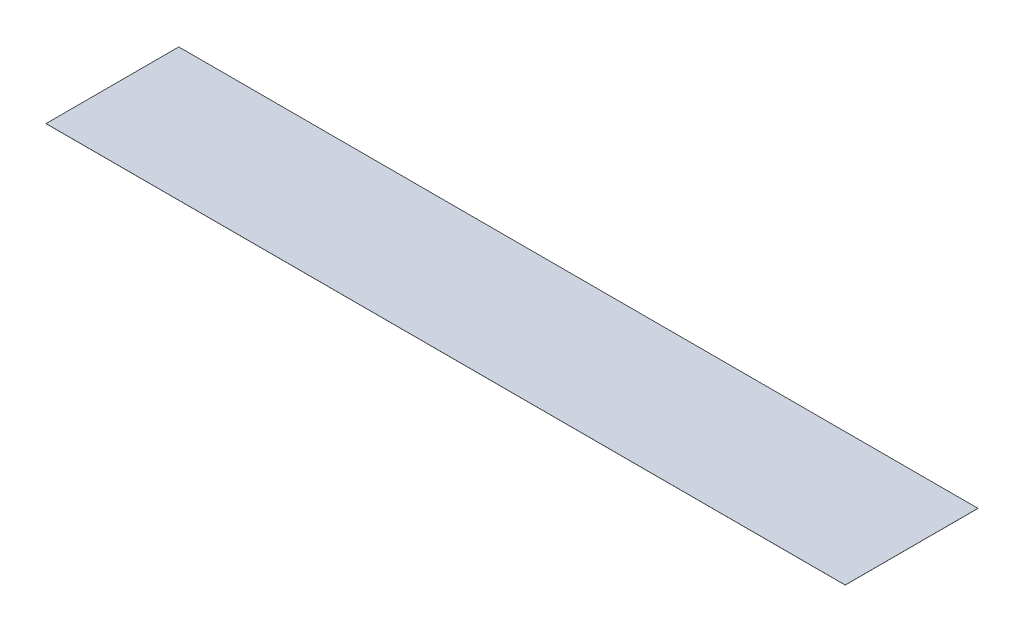
SolidWorks part; units mm, degrees
ref_plane "Plano frontal" through (0, 0, 0) normal (0, 0, 1) x (1, 0, 0)
ref_plane "Plano superior" through (0, 0, 0) normal (0, 1, 0) x (1, 0, 0)
ref_plane "Plano direito" through (0, 0, 0) normal (1, 0, 0) x (0, 0, -1)
sketch "Esboço1" plane through (0, 0, 0) normal (0, 1, 0) x (1, 0, 0)
  line L0 (-1093, 595.536) -> (-1073, 595.536)
  line L1 (0, 0) -> (18.9344, 0)
  line L2 (0, 0) -> (0, 766.8662)
  line L3 (0, 766.8662) -> (18.9344, 766.8662)
  line L4 (18.9344, 0) -> (18.9344, 766.8662)
  line L5 (-381.6968, 766.8662) -> (-362.7624, 766.8662)
  line L6 (-381.6968, 766.8662) -> (-381.6968, 345.536)
  line L7 (-381.6968, 345.536) -> (-362.7624, 345.536)
  line L8 (-362.7624, 766.8662) -> (-362.7624, 345.536)
  line L9 (-858.9344, 645.536) -> (-840, 645.536)
  line L10 (-858.9344, 645.536) -> (-858.9344, 345.536)
  line L11 (-858.9344, 345.536) -> (-840, 345.536)
  line L12 (-840, 645.536) -> (-840, 345.536)
  line L13 (-853.5858, 925.2213) -> (-1253.5858, 925.2213)
  line L14 (-853.5858, 925.2213) -> (-853.5858, 945.2213)
  line L15 (-853.5858, 945.2213) -> (-1253.5858, 945.2213)
  line L16 (-1253.5858, 925.2213) -> (-1253.5858, 945.2213)
  line L17 (-1093, 595.536) -> (-1093, 195.536)
  line L18 (-1093, 195.536) -> (-1073, 195.536)
  line L19 (-1073, 595.536) -> (-1073, 195.536)
  line L21 (-858.9344, 427.7897) -> (-1250.0103, 427.7897)
  line L23 (-858.9344, 407.7897) -> (-1250.0103, 407.7897)
  line L24 (-1250.0103, 427.7897) -> (-1250.0103, 407.7897)
  line L33 (-1439.6613, 239.7512) -> (-1560.0448, 239.7512)
  line L34 (-1439.6613, 239.7512) -> (-1439.6613, 219.7512)
  line L35 (-1439.6613, 219.7512) -> (-1560.0448, 219.7512)
  line L36 (-1560.0448, 239.7512) -> (-1560.0448, 219.7512)
  line L37 (-1627.2015, 576.144) -> (-1607.2015, 576.144)
  line L38 (-1627.2015, 576.144) -> (-1627.2015, 317.0654)
  line L39 (-1627.2015, 317.0654) -> (-1607.2015, 317.0654)
  line L40 (-1607.2015, 576.144) -> (-1607.2015, 317.0654)
  line L41 (-1627.2015, 769.6927) -> (-1607.2015, 769.6927)
  line L42 (-1627.2015, 769.6927) -> (-1627.2015, 1019.6927)
  line L43 (-1627.2015, 1019.6927) -> (-1607.2015, 1019.6927)
  line L44 (-1607.2015, 769.6927) -> (-1607.2015, 1019.6927)
  line L45 (-1714.3168, 276.905) -> (-1834.7003, 276.905)
  line L46 (-1714.3168, 276.905) -> (-1714.3168, 256.905)
  line L47 (-1714.3168, 256.905) -> (-1834.7003, 256.905)
  line L48 (-1834.7003, 276.905) -> (-1834.7003, 256.905)
  arc A6 (-381.6968, 766.8662) -> (18.9344, 766.8662) centre (-181.3812, 766.8662) cw
  arc A7 (-362.7624, 766.8662) -> (0, 766.8662) centre (-181.3812, 766.8662) cw
  arc A8 (-362.7624, 345.536) -> (-858.9344, 345.536) centre (-610.8484, 345.536) cw
  arc A9 (-381.6968, 345.536) -> (-840, 345.536) centre (-610.8484, 345.536) cw
  arc A10 (-840, 645.536) -> (-803.6955, 702.0415) centre (-777.8744, 645.536) cw
  arc A11 (-803.6955, 702.0415) -> (-853.5858, 945.2213) centre (-856.6336, 817.8884) ccw
  arc A12 (-858.9344, 645.536) -> (-814.4955, 717.9247) centre (-777.7563, 645.536) cw
  arc A13 (-814.4955, 717.9247) -> (-853.5858, 925.2213) centre (-864.2122, 815.8835) ccw
  arc A14 (-1093, 595.536) -> (-1188.5366, 677.9223) centre (-1176.2913, 595.536) ccw
  arc A15 (-1188.5366, 677.9223) -> (-1354.3411, 742.8189) centre (-1214.8489, 854.9525) cw
  arc A16 (-1354.3411, 742.8189) -> (-1253.5858, 945.2213) centre (-1257.3278, 820.805) cw
  arc A17 (-1073, 595.536) -> (-1188.5366, 698.0004) centre (-1176.2038, 595.536) ccw
  arc A18 (-1188.5366, 698.0004) -> (-1341.8208, 766.8662) centre (-1207.9995, 859.705) cw
  arc A19 (-1341.8208, 766.8662) -> (-1253.5858, 925.2213) centre (-1258.876, 824.4093) cw
  arc A22 (-1368.7558, 309.7722) -> (-1439.6613, 219.7512) centre (-1474.849, 320.402) cw
  arc A23 (-1388.5562, 309.7722) -> (-1439.6613, 239.7512) centre (-1477.6183, 321.1143) cw
  arc A24 (-1388.5562, 309.7722) -> (-1250.0103, 427.7897) centre (-1254.4723, 292.6965) cw
  arc A25 (-1607.2015, 317.0654) -> (-1560.0448, 239.7512) centre (-1520.2441, 317.0654) ccw
  arc A26 (-1627.2015, 317.0654) -> (-1560.0448, 219.7512) centre (-1523.1159, 317.0654) ccw
  arc A27 (-1368.7558, 309.7722) -> (-1250.0103, 407.7897) centre (-1259.9289, 298.8686) cw
extrude "Ressalto-extrusão15" add sketch "Esboço1" along normal blind 0.01 contours L47 L48 L45 L46
